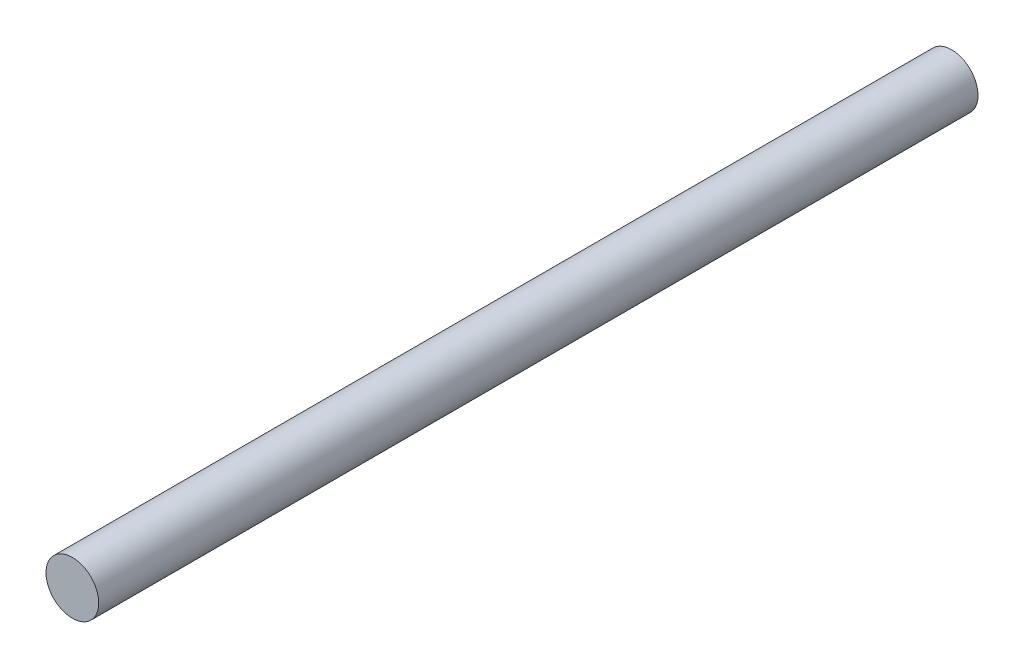
SolidWorks part; units mm, degrees
ref_plane "Front Plane" through (0, 0, 0) normal (0, 0, 1) x (1, 0, 0)
ref_plane "Top Plane" through (0, 0, 0) normal (0, 1, 0) x (1, 0, 0)
ref_plane "Right Plane" through (0, 0, 0) normal (1, 0, 0) x (0, 0, -1)
sketch "Sketch2" plane through (0, 0, -1433.0836) normal (0, 0, -1) x (-1, 0, 0)
  circle A0 centre (0, 0) radius 0.75 construction
  circle A1 centre (0, 0) radius 0.75
extrude "Boss-Extrude2" add sketch "Sketch2" along normal blind 25
